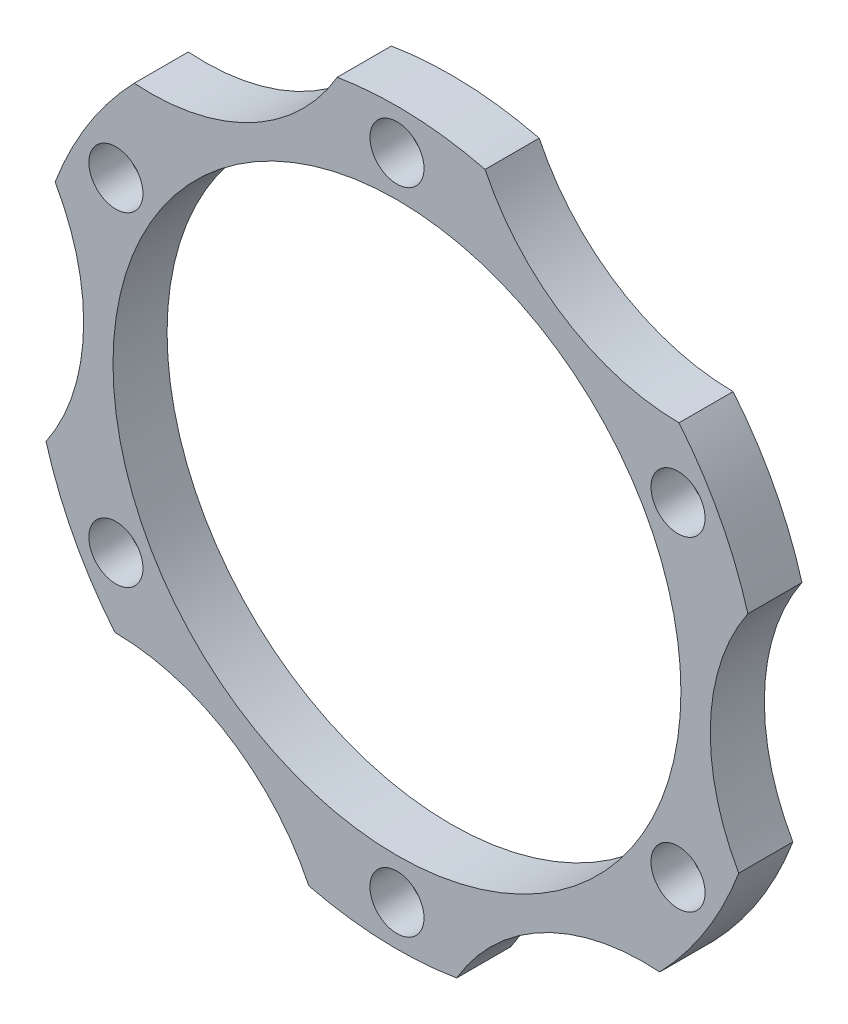
SolidWorks part; units mm, degrees
material "1060 Alaşım"
ref_plane "Ön Düzlem" through (0, 0, 0) normal (0, 0, 1) x (1, 0, 0)
ref_plane "Üst Düzlem" through (0, 0, 0) normal (0, 1, 0) x (1, 0, 0)
ref_plane "Sağ Düzlem" through (0, 0, 0) normal (1, 0, 0) x (0, 0, -1)
sketch "Çizim1" plane through (0, 0, 0) normal (0, 0, 1) x (1, 0, 0)
  circle A0 centre (0, 0) radius 52.5
  circle A1 centre (0, 0) radius 67.5
  circle A2 centre (0, 60) radius 2.75
  circle A3 centre (51.9615, 30) radius 2.75
  circle A4 centre (51.9615, -30) radius 2.75
  circle A5 centre (0, -60) radius 2.75
  circle A6 centre (-51.9615, -30) radius 2.75
  circle A7 centre (-51.9615, 30) radius 2.75
  point P19 (0, 0)
  dimension "D1" = 105
  dimension "D2" = 135
  dimension "D4" = 5.5
  dimension "D3" = 60
  dimension "D5" = 6
extrude "Yükseklik-Ekstrüzyon1" add sketch "Çizim1" along normal blind 10
sketch "Çizim2" plane through (0, 0, 0) normal (0, 0, -1) x (-1, 0, 0)
  line L0 (-61.2121, 43.8526) -> (-15, 68.5005)
  line L1 (7.3714, 74.9375) -> (51.8232, 47.2406)
  line L2 (68.5835, 31.0849) -> (66.8232, -21.2599)
  line L3 (61.2121, -43.8526) -> (15, -68.5005)
  line L4 (-7.3714, -74.9375) -> (-51.8232, -47.2406)
  line L5 (-68.5835, -31.0849) -> (-66.8232, 21.2599)
  arc A0 (-15, 68.5005) -> (-61.2121, 43.8526) centre (-52.3355, 82.8552) cw
  arc A1 (51.8232, 47.2406) -> (7.3714, 74.9375) centre (45.587, 86.7515) cw
  arc A2 (66.8232, -21.2599) -> (68.5835, 31.0849) centre (97.9225, 3.8963) cw
  arc A3 (15, -68.5005) -> (61.2121, -43.8526) centre (52.3355, -82.8552) cw
  arc A4 (-51.8232, -47.2406) -> (-7.3714, -74.9375) centre (-45.587, -86.7515) cw
  arc A5 (-66.8232, 21.2599) -> (-68.5835, -31.0849) centre (-97.9225, -3.8963) cw
  circle A7 centre (0, 0) radius 67.5 construction
  circle A8 centre (0, 60) radius 2.75 construction
  point P23 (0, 0)
  dimension "D1" = 40
  dimension "D4" = 15
  dimension "D2" = 98
  dimension "D3" = 6
extrude "Kes-Ekstrüzyon1" cut sketch "Çizim2" against normal blind 14
sketch "Çizim3" plane through (0, 0, 10) normal (0, 0, 1) x (1, 0, 0)
  circle A0 centre (0, 60) radius 5
  circle A1 centre (51.9615, 30) radius 5
  circle A2 centre (51.9615, -30) radius 5
  circle A3 centre (0, -60) radius 5
  circle A4 centre (-51.9615, -30) radius 5
  circle A5 centre (-51.9615, 30) radius 5
  point P16 (0, 0)
  dimension "D1" = 10
  dimension "D2" = 6
extrude "Kes-Ekstrüzyon2" cut sketch "Çizim3" against normal blind 7
